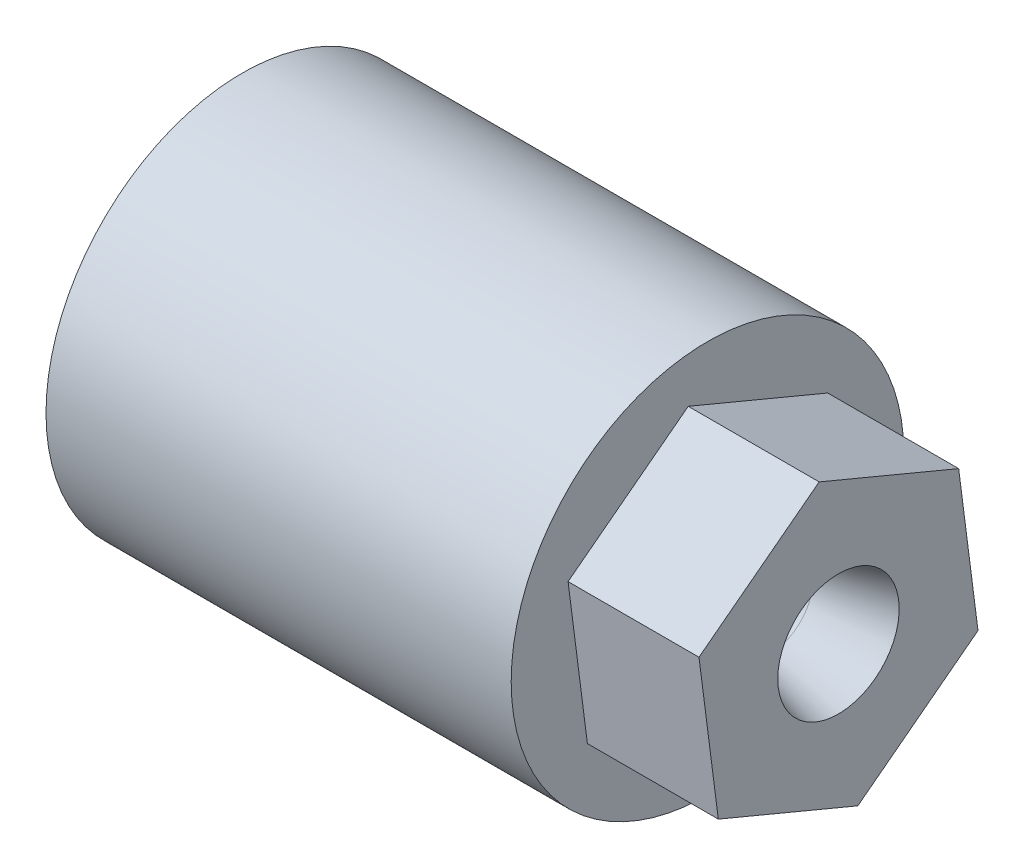
SolidWorks part; units mm, degrees
ref_plane "Front Plane" through (0, 0, 0) normal (0, 0, 1) x (1, 0, 0)
ref_plane "Top Plane" through (0, 0, 0) normal (0, 1, 0) x (1, 0, 0)
ref_plane "Right Plane" through (0, 0, 0) normal (1, 0, 0) x (0, 0, -1)
sketch "Sketch1" plane through (0, 0, 0) normal (0, 0, 1) x (1, 0, 0)
  line L0 (0, 0) -> (3.5131, 0) construction
  line L1 (0.2104, 2.0597) -> (3.5131, 2.9446)
  line L2 (-2.1553, 2.9247) -> (-4.048, 4.8174)
  line L3 (-25.4, 5.7474) -> (-25.4, 9.525)
  line L4 (-6.293, 5.7474) -> (-25.4, 5.7474)
  line L5 (-25.4, 9.525) -> (-9.1869, 9.525)
  line L6 (3.5131, 9.525) -> (3.5131, 2.9446)
  line L8 (-9.1869, 9.525) -> (3.5131, 9.525)
  arc A0 (-2.1553, 2.9247) -> (0, 2.032) centre (0, 5.08) ccw
  arc A1 (0, 2.032) -> (0.2104, 2.0597) centre (0, 2.8448) ccw
  arc A2 (-4.048, 4.8174) -> (-6.293, 5.7474) centre (-6.293, 2.5724) ccw
  dimension "D3" = 3.048
  dimension "D4" = 0.8128
  dimension "D11" = 3.175
  dimension "D1" = 2.032
  dimension "D2" = 3.5131
  dimension "D5" = 2.9446
  dimension "D6" = 15
  dimension "D7" = 45
  dimension "D8" = 5.7474
  dimension "D9" = 25.4
  dimension "D10" = 9.525
  dimension "D13" = 12.7
revolve "Revolve1" add sketch "Sketch1" angle 360 about L0
sketch "Sketch3" plane through (3.5131, 0, 0) normal (1, 0, 0) x (0, 0, -1)
  line L1 (0.9374, -7.2722) -> (6.7666, -2.8242)
  line L2 (6.7666, -2.8242) -> (5.8292, 4.4479)
  line L3 (5.8292, 4.4479) -> (-0.9374, 7.2722)
  line L4 (-0.9374, 7.2722) -> (-6.7666, 2.8242)
  line L5 (-6.7666, 2.8242) -> (-5.8292, -4.4479)
  line L6 (-5.8292, -4.4479) -> (0.9374, -7.2722)
  circle A0 centre (0, 0) radius 6.35 construction
  circle M7 centre (0, 0) radius 9.525
  dimension "D1" = 12.7
extrude "Cut-Extrude2" cut sketch "Sketch3" against normal blind 6.35 contours L6 L5 L4 L3 L2 L1 M7
equation "\"D3@Sketch1\"= 1.5 * \"D1@Sketch1\""
equation "\"D4@Sketch1\"=.4 * \"D1@Sketch1\""
equation "\"D5@Sketch1\"=\"D1@Sketch1\" * ( 2.1 ) ^ .5"
equation "\"D8@Sketch1\"=\"D1@Sketch1\" * ( 8 ) ^ .5"
equation "\"er\"= 4"
